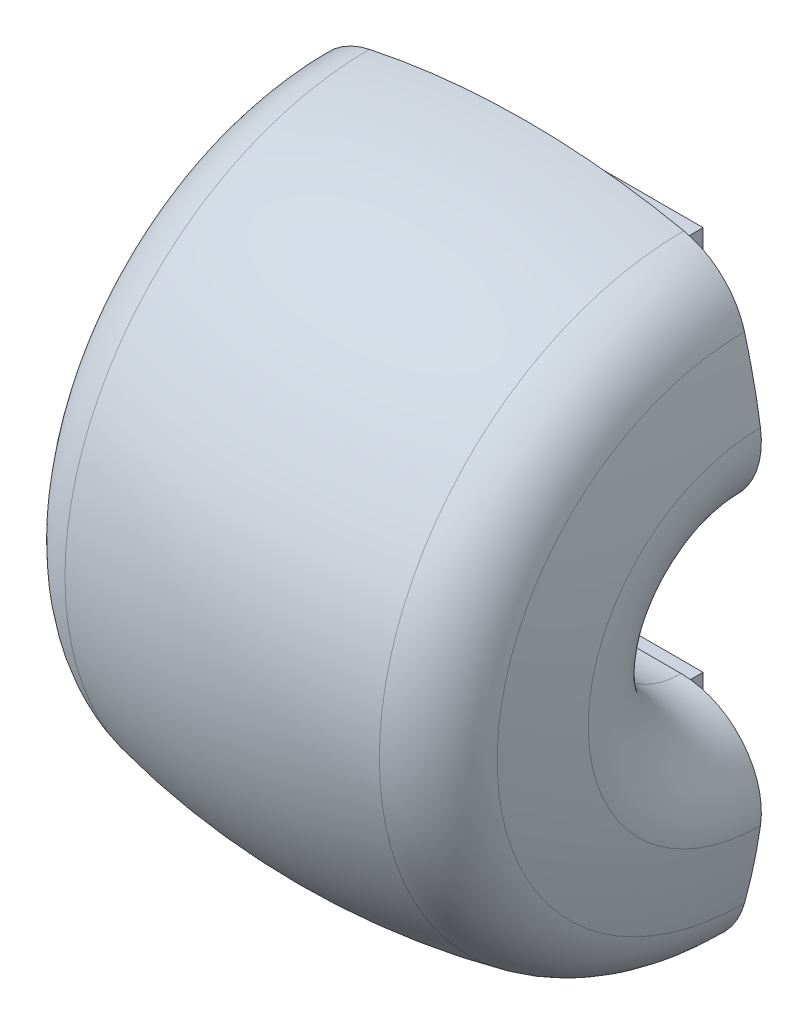
SolidWorks part; units mm, degrees
ref_plane "前视基准面" through (0, 0, 0) normal (0, 0, 1) x (1, 0, 0)
ref_plane "上视基准面" through (0, 0, 0) normal (0, 1, 0) x (1, 0, 0)
ref_plane "右视基准面" through (0, 0, 0) normal (1, 0, 0) x (0, 0, -1)
other "Configuration Table"
sketch "草图1" plane through (0, 0, 0) normal (0, 0, 1) x (1, 0, 0)
  line L0 (-17.5, 0) -> (17.5, 0) construction
  line L1 (0, 20) -> (0, 5) construction
  line L3 (-15, 5) -> (15, 5)
  arc A2 (12.6691, 18.2758) -> (-12.6691, 18.2758) centre (0, -27.4063) ccw
  arc A3 (-15, 5) -> (-12.6691, 18.2758) centre (23.9716, 5) cw
  arc A4 (15, 5) -> (12.6691, 18.2758) centre (-23.9716, 5) ccw
  point P3 (0, 0)
  dimension "D4" = 30
revolve "旋转1" add sketch "草图1" angle 180 about L0
fillet "圆角1" radius 5 2 edges at (12.6691, 0, 18.2758) (-12.6691, 0, 18.2758)
fillet "圆角2" radius 5 2 edges at (15, 0, 5) (-15, 0, 5)
sketch "草图3" plane through (0, 0, 0) normal (0, 0, -1) x (-1, 0, 0)
  line L1 (-5, 13.75) -> (5, 13.75)
  line L2 (-5, 13.75) -> (-5, 10.25)
  line L3 (-5, 10.25) -> (5, 10.25)
  line L4 (5, 13.75) -> (5, 10.25)
  line L5 (-5, 13.75) -> (5, 10.25) construction
  line L6 (-5, 10.25) -> (5, 13.75) construction
  line L7 (-5, -10.25) -> (5, -10.25)
  line L8 (-5, -10.25) -> (-5, -13.75)
  line L9 (-5, -13.75) -> (5, -13.75)
  line L10 (5, -10.25) -> (5, -13.75)
  line L11 (-5, -10.25) -> (5, -13.75) construction
  line L12 (-5, -13.75) -> (5, -10.25) construction
  point P0 (0, 12)
  point P5 (0, -12)
  dimension "D1" = 12
  dimension "D2" = 3.5
  dimension "D3" = 10
  dimension "D4" = 3.5
  dimension "D5" = 12
  dimension "D6" = 10
extrude "凸台-拉伸1" add sketch "草图3" along normal blind 6
